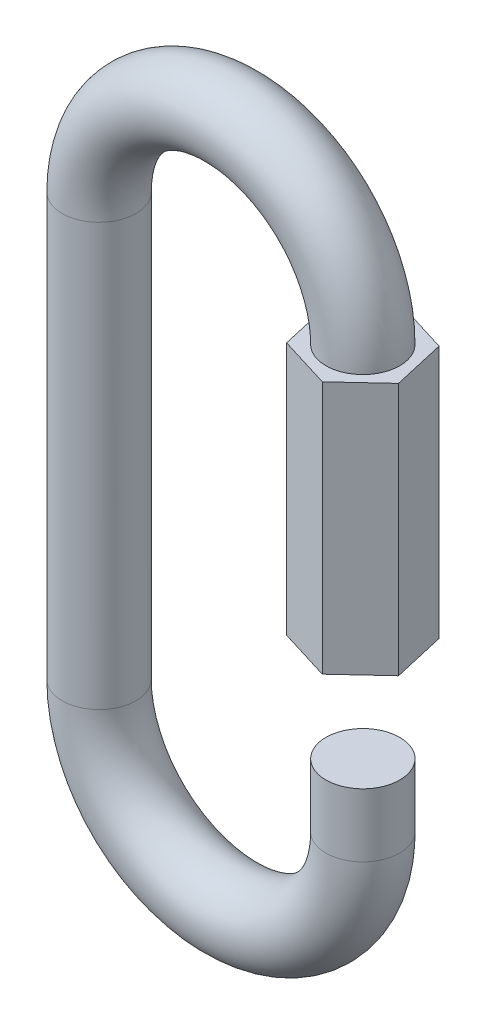
SolidWorks part; units mm, degrees
material "AISI 1020"
ref_plane "Front Plane" through (0, 0, 0) normal (0, 0, 1) x (1, 0, 0)
ref_plane "Top Plane" through (0, 0, 0) normal (0, 1, 0) x (1, 0, 0)
ref_plane "Right Plane" through (0, 0, 0) normal (1, 0, 0) x (0, 0, -1)
sketch "Sketch1" plane through (0, 0, 0) normal (0, 1, 0) x (1, 0, 0)
  circle A0 centre (0, 0) radius 3.5
  dimension "D1" = 7
sketch "Sketch2" plane through (0, 0, 0) normal (0, 0, 1) x (1, 0, 0)
  line L0 (0, 0) -> (0, 24)
  line L1 (3.5, 0) -> (-3.5, 0) construction
  line L2 (-25, 24) -> (-25, -16)
  line L3 (0, -16) -> (0, -10)
  arc A0 (0, 24) -> (-25, 24) centre (-12.5, 24) ccw
  arc A1 (-25, -16) -> (0, -16) centre (-12.5, -16) ccw
  point P9 (-12.5, 36.5)
  point P12 (-12.5, -28.5)
  point P13 (-12.5, -14.9767)
  point P14 (0, 24)
  point P15 (0, 24)
  dimension "D1" = 65
  dimension "D2" = 25
  dimension "D3" = 10
  dimension "D4" = 24
sweep "Sweep1" add profiles "Sketch1" path "Sketch2"
sketch "Sketch3" plane through (0, 0, 0) normal (0, -1, 0) x (1, 0, 0)
  line L1 (4.8877, 1.5042) -> (1.1411, 4.985)
  line L2 (1.1411, 4.985) -> (-3.7466, 3.4808)
  line L3 (-3.7466, 3.4808) -> (-4.8877, -1.5042)
  line L4 (-4.8877, -1.5042) -> (-1.1411, -4.985)
  line L5 (-1.1411, -4.985) -> (3.7466, -3.4808)
  line L6 (3.7466, -3.4808) -> (4.8877, 1.5042)
  circle A0 centre (0, 0) radius 4.4288 construction
extrude "Boss-Extrude1" add sketch "Sketch3" against normal blind 24
